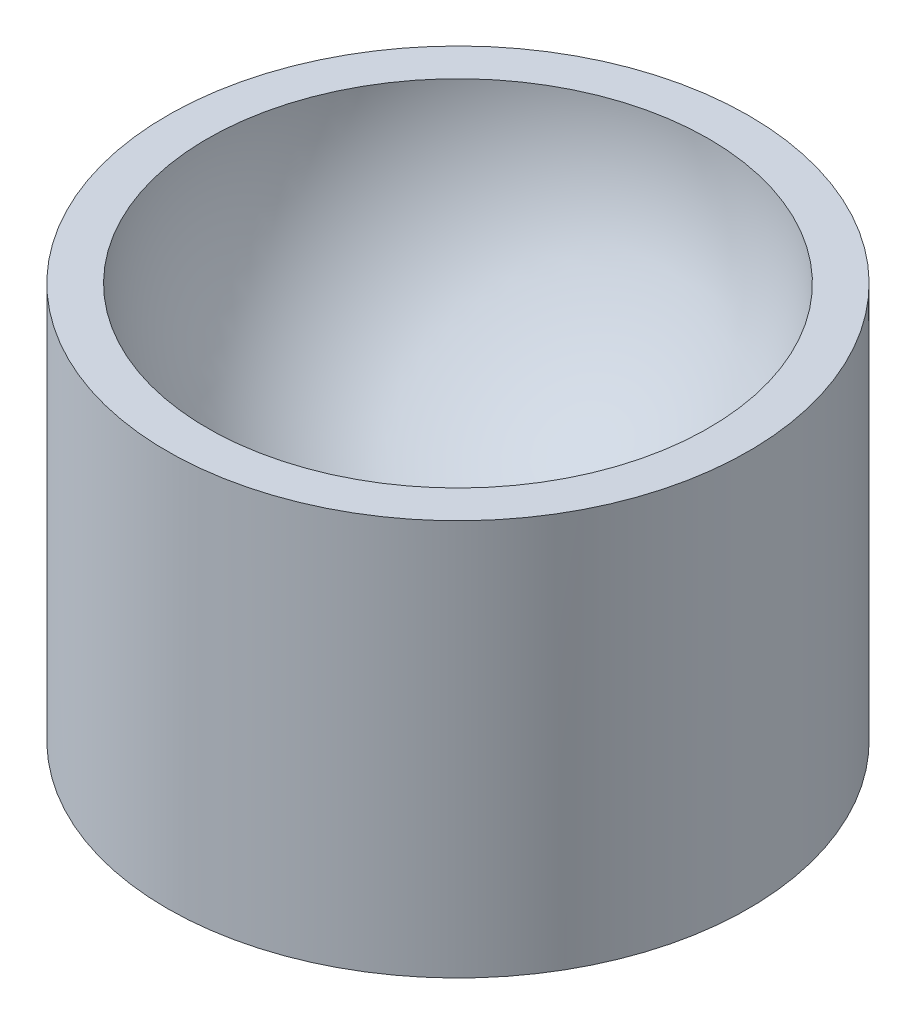
SolidWorks part; units mm, degrees
ref_plane "Front Plane" through (0, 0, 0) normal (0, 0, 1) x (1, 0, 0)
ref_plane "Top Plane" through (0, 0, 0) normal (0, 1, 0) x (1, 0, 0)
ref_plane "Right Plane" through (0, 0, 0) normal (1, 0, 0) x (0, 0, -1)
sketch "Sketch2" plane through (0, 0, 0) normal (0, 1, 0) x (1, 0, 0)
  line L1 (0, 7.5056) -> (-6.5, 3.7528)
  line L2 (-6.5, 3.7528) -> (-6.5, -3.7528)
  line L3 (-6.5, -3.7528) -> (0, -7.5056)
  line L4 (0, -7.5056) -> (6.5, -3.7528)
  line L5 (6.5, -3.7528) -> (6.5, 3.7528)
  line L6 (6.5, 3.7528) -> (0, 7.5056)
  circle A0 centre (0, 0) radius 29
  circle A1 centre (0, 0) radius 6.5 construction
  dimension "D1" = 58
  dimension "D2" = 13
extrude "Boss-Extrude1" add sketch "Sketch2" along normal blind 11.5
sketch "Sketch3" plane through (0, 0, 0) normal (0, -1, 0) x (1, 0, 0)
  circle A0 centre (0, 0) radius 8
  dimension "D1" = 16
extrude "Cut-Extrude1" cut sketch "Sketch3" against normal blind 7
sketch "Sketch4" plane through (0, 0, 0) normal (0, 0, 1) x (1, 0, 0)
  line L0 (0, 0) -> (0, 39.5) construction
  line L1 (4.05, 14.8302) -> (4.05, 11.5)
  line L2 (4.05, 11.5) -> (29, 11.5)
  line L4 (29, 11.5) -> (-29, 11.5) construction
  line L5 (29, 11.5) -> (29, 39.5)
  line L6 (29, 39.5) -> (25, 39.5)
  arc A0 (4.05, 14.8302) -> (25, 39.5) centre (0, 39.5) ccw
  dimension "D1" = 50
  dimension "D2" = 3
  dimension "D3" = 4.05
revolve "Revolve1" add sketch "Sketch4" angle 360 about L0
